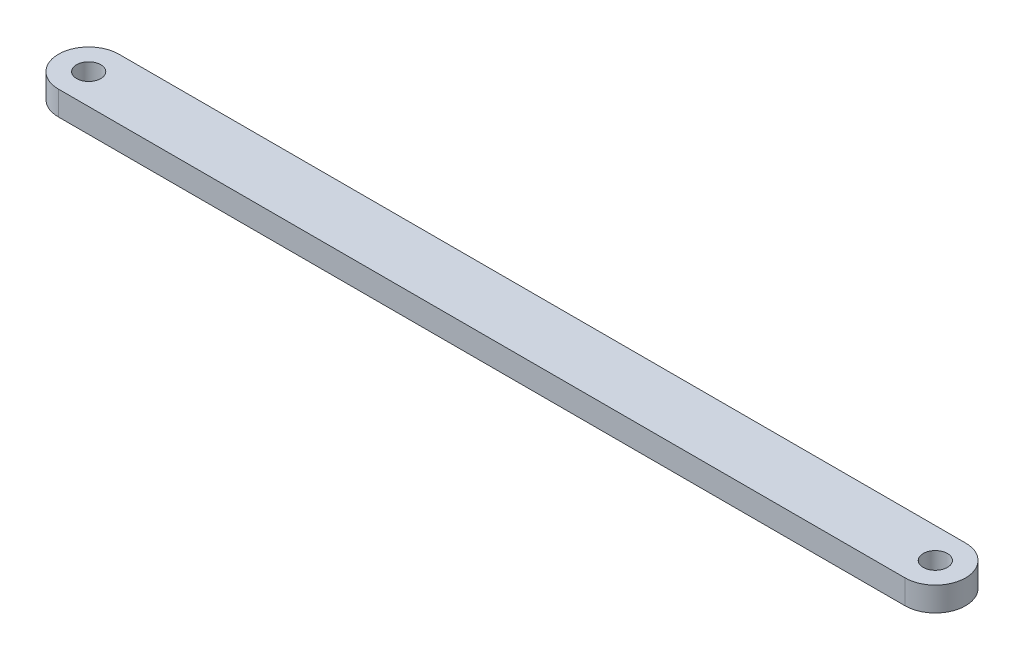
SolidWorks part; units mm, degrees
ref_plane "Front Plane" through (0, 0, 0) normal (0, 0, 1) x (1, 0, 0)
ref_plane "Top Plane" through (0, 0, 0) normal (0, 1, 0) x (1, 0, 0)
ref_plane "Right Plane" through (0, 0, 0) normal (1, 0, 0) x (0, 0, -1)
sketch "Sketch1" plane through (0, 0, 0) normal (0, 1, 0) x (1, 0, 0)
  line L0 (0, 0) -> (70, 0) construction
  line L1 (0, 2.5) -> (70, 2.5)
  line L2 (0, -2.5) -> (70, -2.5)
  arc A0 (0, 2.5) -> (0, -2.5) centre (0, 0) ccw
  arc A1 (70, -2.5) -> (70, 2.5) centre (70, 0) ccw
  circle A2 centre (0, 0) radius 1
  circle A3 centre (70, 0) radius 1
  point P3 (35, 0)
  dimension "D2" = 2.5
  dimension "D4" = 2
  dimension "D5" = 2
  dimension "D1" = 70
extrude "Boss-Extrude1" add sketch "Sketch1" along normal blind 2
